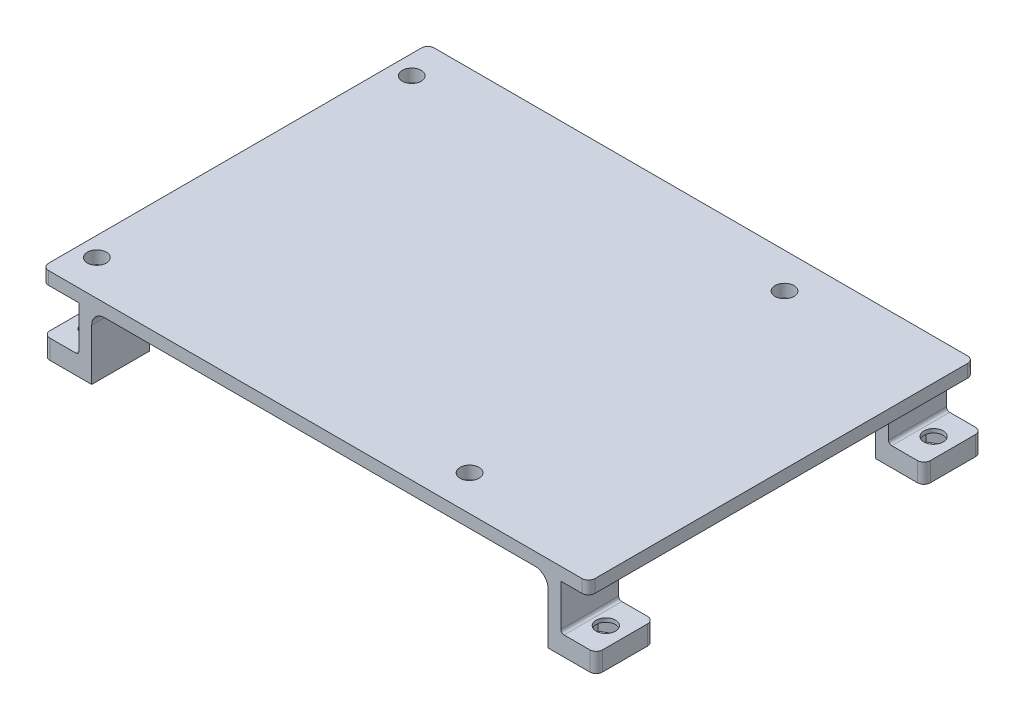
SolidWorks part; units mm, degrees
ref_plane "前基準面" through (0, 0, 0) normal (0, 0, 1) x (1, 0, 0)
ref_plane "上基準面" through (0, 0, 0) normal (0, 1, 0) x (1, 0, 0)
ref_plane "右基準面" through (0, 0, 0) normal (1, 0, 0) x (0, 0, -1)
sketch "草圖1" plane through (0, 0, 0) normal (0, 0, 1) x (1, 0, 0)
  line L0 (-133.4262, 0) -> (6537.8852, 0) construction
  line L1 (0, -133.4262) -> (0, 6537.8852) construction
  line L2 (-43, 0) -> (-43, 3)
  line L3 (-43, 3) -> (-37.5, 3)
  line L4 (-37.5, 3) -> (-37.5, 10)
  line L6 (37.5, 10) -> (37.5, 3)
  line L7 (37.5, 3) -> (43, 3)
  line L8 (43, 3) -> (43, 0)
  line L10 (-35.5, 0) -> (-35.5, 10)
  line L11 (-35.5, 10) -> (35.5, 10)
  line L12 (35.5, 10) -> (35.5, 0)
  line L13 (-43, 0) -> (-35.5, 0)
  line L14 (35.5, 0) -> (43, 0)
  line L16 (-43.2, 12) -> (-43.2, 10)
  line L17 (-37.5, 10) -> (-43.2, 10)
  line L18 (-43.2, 12) -> (41.8, 12)
  line L19 (41.8, 12) -> (41.8, 10)
  line L20 (41.8, 10) -> (37.5, 10)
  dimension "D1" = 2
  dimension "D2" = 10
  dimension "D3" = 71
  dimension "D4" = 86
  dimension "D5" = 2
  dimension "D6" = 3
  dimension "D7" = 85
  dimension "D8" = 5.7
extrude "填料-伸長1" add sketch "草圖1" along normal mid plane 60
sketch "草圖8" plane through (0, 0, 0) normal (0, 0, 1) x (1, 0, 0)
  line L0 (41.8, 12) -> (-43.2, 12) construction
  line L2 (35.5, 10) -> (35.5, 0) construction
  line L4 (-35.5, 10) -> (35.5, 10) construction
  line L5 (-35.5, 0) -> (-35.5, 10) construction
  line L6 (37.5, 12) -> (-37.5072, 12)
  line L7 (35.5, 0) -> (43, 0) construction
  line L8 (35.5, 10) -> (35.5, 0)
  line L9 (-35.5, 0) -> (-37.5072, 0)
  line L10 (-35.5, 10) -> (35.5, 10)
  line L11 (-35.5, 0) -> (-35.5, 10)
  line L12 (37.5, 0) -> (37.5, 12)
  line L13 (35.5, 0) -> (37.5, 0)
  line L14 (-37.5072, 12) -> (-37.5072, 0)
sketch "草圖2" plane through (0, 0, 0) normal (1, 0, 0) x (0, 0, -1)
  line L0 (-1000, 0) -> (49000, 0) construction
  line L1 (0, -1000) -> (0, 49000) construction
  line L3 (-21, -6) -> (21, -6)
  line L4 (-21, -6) -> (-21, 6)
  line L5 (-21, 6) -> (21, 6)
  line L6 (21, -6) -> (21, 6)
  line L7 (-21, -6) -> (21, 6) construction
  line L8 (-21, 6) -> (21, -6) construction
  point P4 (0, 0)
  dimension "D1" = 42
  dimension "D2" = 12
extrude "除料-伸長1" cut sketch "草圖2" against normal through all both and the other way through all
sketch "草圖3" plane through (0, 0, 0) normal (0, 1, 0) x (1, 0, 0)
  line L0 (-40, -1017.5) -> (-40, 48982.5) construction
  line L2 (40, -1017.5) -> (40, 48982.5) construction
  line L4 (-1031.5, 25.5) -> (48968.5, 25.5) construction
  line L5 (0, -1000) -> (0, 49000) construction
  line L6 (-1031.5, -25.5) -> (48968.5, -25.5) construction
  line L8 (-1000, 0) -> (49000, 0) construction
  line L9 (-43.2, -30) -> (-37.5, -30) construction
  line L10 (35.5, -30) -> (43, -30) construction
  circle A0 centre (-40, 25.5) radius 1.5
  circle A1 centre (40, 25.5) radius 1.5
  circle A2 centre (40, -25.5) radius 1.5
  circle A3 centre (-40, -25.5) radius 1.5
  point P12 (-40, -30)
  point P16 (40, -30)
  dimension "D1" = 3
  dimension "D2" = 51
  dimension "D3" = 80
extrude "除料-伸長4" cut sketch "草圖3" along normal up to next contours A0 | A1 | A3 | A2
sketch "草圖5" plane through (0, 12, 0) normal (0, 1, 0) x (1, 0, 0)
  line L0 (-1000, 0) -> (49000, 0) construction
  line L1 (-1033.1907, 24.5) -> (48966.8093, 24.5) construction
  line L2 (-1033.1907, -24.5) -> (48966.8093, -24.5) construction
  line L3 (-40.2, 24.5) -> (-40.2, -24.5) construction
  line L4 (17.8, 24.5) -> (17.8, -24.5) construction
  line L5 (-43.2, -30) -> (-43.2, 30) construction
  circle A0 centre (-40.2, 24.5) radius 1.475
  circle A1 centre (-40.2, -24.5) radius 1.475
  circle A2 centre (17.8, 24.5) radius 1.475
  circle A3 centre (17.8, -24.5) radius 1.475
  dimension "D3" = 2.95
  dimension "D1" = 49
  dimension "D2" = 24.5
  dimension "D4" = 58
  dimension "D5" = 3
extrude "除料-伸長5" cut sketch "草圖5" against normal blind 5
ref_plane "平面1" through (0, 3, 0) normal (0, 1, 0) x (1, 0, 0)
sketch "草圖16" plane through (0, 0, 0) normal (0, -1, 0) x (1, 0, 0)
  line L0 (-59.8233, 0) -> (72.7296, 0) construction
  line L1 (-40, 22.2091) -> (-37.15, 23.8546)
  line L2 (-37.15, 23.8546) -> (-37.15, 27.1454)
  line L3 (-37.15, 27.1454) -> (-40, 28.7909)
  line L4 (-40, 28.7909) -> (-42.85, 27.1454)
  line L5 (-42.85, 27.1454) -> (-42.85, 23.8546)
  line L6 (-42.85, 23.8546) -> (-40, 22.2091)
  line L7 (-42.85, -23.8546) -> (-40, -22.2091)
  line L8 (0, 58.8179) -> (0, -48.0944) construction
  line L9 (-42.85, -27.1454) -> (-42.85, -23.8546)
  line L10 (-40, -28.7909) -> (-42.85, -27.1454)
  line L11 (-37.15, -27.1454) -> (-40, -28.7909)
  line L12 (-37.15, -23.8546) -> (-37.15, -27.1454)
  line L13 (-40, -22.2091) -> (-37.15, -23.8546)
  line L14 (40, -22.2091) -> (37.15, -23.8546)
  line L15 (37.15, -23.8546) -> (37.15, -27.1454)
  line L16 (37.15, -27.1454) -> (40, -28.7909)
  line L17 (40, -28.7909) -> (42.85, -27.1454)
  line L18 (42.85, -27.1454) -> (42.85, -23.8546)
  line L19 (42.85, -23.8546) -> (40, -22.2091)
  line L20 (42.85, 23.8546) -> (40, 22.2091)
  line L21 (42.85, 27.1454) -> (42.85, 23.8546)
  line L22 (40, 28.7909) -> (42.85, 27.1454)
  line L23 (37.15, 27.1454) -> (40, 28.7909)
  line L24 (37.15, 23.8546) -> (37.15, 27.1454)
  line L25 (40, 22.2091) -> (37.15, 23.8546)
  circle A0 centre (-40, 25.5) radius 2.85 construction
  circle A1 centre (-40, -25.5) radius 2.85 construction
  circle A2 centre (40, -25.5) radius 2.85 construction
  circle A3 centre (40, 25.5) radius 2.85 construction
  dimension "D1" = 5.7
extrude "除料-伸長7" cut sketch "草圖16" against normal blind 2.4
fillet "圓角1" radius 1 12 edges at (41.8, 11, -30) (43, 1.5, -30) (43, 1.5, -21) (43, 1.5, 21) (43, 1.5, 30) (41.8, 11, 30) (-43.2, 11, -30) (-43, 1.5, -30) (-43, 1.5, -21) (-43, 1.5, 21) (-43, 1.5, 30) (-43.2, 11, 30)
fillet "圓角5" radius 0.5 4 edges at (37.5, 3, -25.5) (37.5, 3, 25.5) (-37.5, 3, -25.5) (-37.5, 3, 25.5)
fillet "圓角7" radius 2 2 edges at (35.5, 10, 0) (-35.5, 10, 0)
